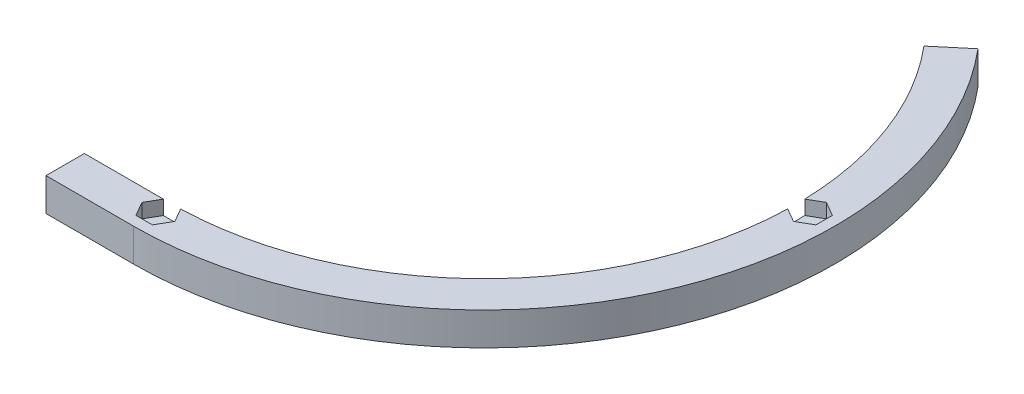
SolidWorks part; units mm, degrees
ref_plane "Front Plane" through (0, 0, 0) normal (0, 0, 1) x (1, 0, 0)
ref_plane "Top Plane" through (0, 0, 0) normal (0, 1, 0) x (1, 0, 0)
ref_plane "Right Plane" through (0, 0, 0) normal (1, 0, 0) x (0, 0, -1)
sketch "Sketch1" plane through (0, 0, 0) normal (0, 1, 0) x (1, 0, 0)
  line L0 (0, -142.5) -> (0, -160)
  line L1 (0, 0) -> (122.5671, 102.846)
  line L2 (0, 0) -> (0, -160) construction
  circle A0 centre (0, 0) radius 142.5
  circle A1 centre (0, 0) radius 136 construction
  circle A2 centre (0, 0) radius 148.7 construction
  circle A3 centre (0, 0) radius 160
  dimension "D1" = 285
  dimension "D2" = 272
  dimension "D4" = 320
  dimension "D5" = 130
  dimension "D3" = 12.7
extrude "Boss-Extrude1" add sketch "Sketch1" along normal blind 15 contours L0 A3 L1 A0
sketch "Sketch2" plane through (0, 0, 0) normal (-1, 0, 0) x (0, 0, 1)
  line L4 (142.5, 0) -> (160, 0)
  line L5 (160, 0) -> (160, 15)
  line L6 (160, 15) -> (142.5, 15)
  line L7 (142.5, 15) -> (142.5, 0)
  line L8 (142.5, 0) -> (160, 0)
  line L9 (160, 0) -> (160, 15)
  line L10 (160, 15) -> (142.5, 15)
  line L11 (142.5, 15) -> (142.5, 0)
  dimension "D1" = 0
extrude "Boss-Extrude2" add sketch "Sketch2" along normal blind 40
sketch "Sketch3" plane through (0, 15, 0) normal (0, 1, 0) x (1, 0, 0)
  line L0 (0, -142.5) -> (0, -160) construction
  line L3 (-3.7528, -142.2) -> (-7.5056, -148.7)
  line L4 (-7.5056, -148.7) -> (-3.7528, -155.2)
  line L5 (-3.7528, -155.2) -> (3.7528, -155.2)
  line L6 (3.7528, -155.2) -> (7.5056, -148.7)
  line L7 (7.5056, -148.7) -> (3.7528, -142.2)
  line L8 (3.7528, -142.2) -> (-3.7528, -142.2)
  line L9 (142.2, 3.7528) -> (142.2, -3.7528)
  line L10 (142.2, -3.7528) -> (148.7, -7.5056)
  line L11 (148.7, -7.5056) -> (155.2, -3.7528)
  line L12 (155.2, -3.7528) -> (155.2, 3.7528)
  line L13 (155.2, 3.7528) -> (148.7, 7.5056)
  line L14 (148.7, 7.5056) -> (142.2, 3.7528)
  circle A2 centre (0, -148.7) radius 6.5 construction
  circle A3 centre (148.7, 0) radius 6.5 construction
  circle A4 centre (0, 0) radius 148.7 construction
  point P0 (0, -147.3821)
  point P14 (143.9585, 0)
  dimension "D1" = 13
  dimension "D2" = 13
extrude "Cut-Extrude1" cut sketch "Sketch3" against normal blind 6.5
